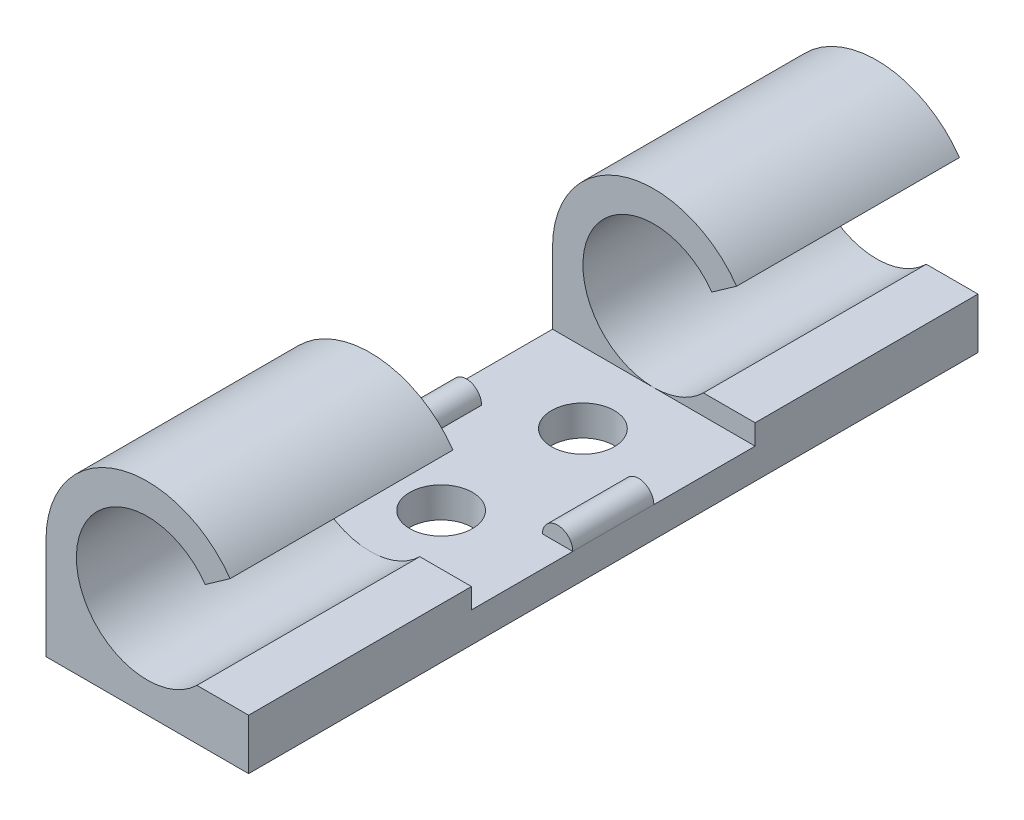
SolidWorks part; units mm, degrees
ref_plane "Plano frontal" through (0, 0, 0) normal (0, 0, 1) x (1, 0, 0)
ref_plane "Plano superior" through (0, 0, 0) normal (0, 1, 0) x (1, 0, 0)
ref_plane "Plano direito" through (0, 0, 0) normal (1, 0, 0) x (0, 0, -1)
sketch "Esboço1" plane through (0, 0, 0) normal (0, 0, 1) x (1, 0, 0)
  line L0 (-5, 0) -> (5, 0)
  line L1 (-5, 5) -> (5, 5)
  line L2 (-5, 5) -> (-5, -5)
  line L3 (-5, -5) -> (5, -5)
  line L4 (5, 5) -> (5, -5)
  line L5 (-5, 5) -> (5, -5) construction
  line L6 (-5, -5) -> (5, 5) construction
  circle A0 centre (0, 0) radius 5
  circle A2 centre (0, 0) radius 3.5
  point P0 (0, 0)
  point P12 (0, 0)
  dimension "D3" = 7
  dimension "D1" = 10
  dimension "D2" = 10
extrude "Ressalto-extrusão1" add sketch "Esboço1" along normal blind 11 contours A0 L2 L3 | A0 L3 L4 | A2 L0 A0 | A2 L0 A0
sketch "Esboço2" plane through (0, 0, 11) normal (0, 0, 1) x (1, 0, 0)
  line L0 (5, 0) -> (5, -5) construction
  line L1 (-5, -5) -> (5, -5)
  line L2 (-5, -5) -> (-5, -3.5)
  line L3 (-5, -3.5) -> (5, -3.5)
  line L4 (5, -5) -> (5, -3.5)
  line L5 (-5, -5) -> (5, -3.5) construction
  line L6 (-5, -3.5) -> (5, -5) construction
  circle A0 centre (0, 0) radius 3.5 construction
  point P4 (0, -4.25)
extrude "Ressalto-extrusão2" add sketch "Esboço2" along normal blind 7
sketch "Esboço3" plane through (0, 0, 18) normal (0, 0, 1) x (1, 0, 0)
  line L0 (5, -3.5) -> (0, -3.5) construction
  line L1 (5, -3.5) -> (0, -3.5) construction
  line L2 (0, 0) -> (0, -0.723) construction
  arc A0 (5, -3.5) -> (3.5, -3.5) centre (4.25, -3.5) ccw
  arc A1 (3.5, -3.5) -> (5, -3.5) centre (4.25, -3.5) ccw construction
  arc A2 (-5, -3.5) -> (-3.5, -3.5) centre (-4.25, -3.5) cw
  line M5 (5, -3.5) -> (-5, -3.5)
  dimension "D1" = 1.5
extrude "Ressalto-extrusão3" add sketch "Esboço3" against normal blind 2 contours A0 M5 | A2 M5
mirror "Espelhar1" about plane through (0, 0, 18) normal (0, 0, -1) of "Ressalto-extrusão2", "Ressalto-extrusão1", "Ressalto-extrusão3"
sketch "Esboço4" plane through (0, -3.5, 0) normal (0, 1, 0) x (1, 0, 0)
  line L0 (0, -11) -> (0, -18) construction
  line L2 (-3.5, -18) -> (3.5, -18) construction
  line L3 (-3.5, -16) -> (-3.5, -20) construction
  line L4 (3.5, -16) -> (3.5, -20) construction
  line L5 (-5, -11) -> (5, -11) construction
  circle A0 centre (0, -14.5) radius 1.55
  circle A1 centre (0, -21.5) radius 1.55
  point P13 (0, 0)
  dimension "D1" = 3.1
extrude "Corte-extrusão1" cut sketch "Esboço4" against normal blind 2
sketch "Esboço5" plane through (0, 0, 36) normal (0, 0, 1) x (1, 0, 0)
  line L0 (5, -2.5) -> (2.4495, -2.5)
  line L1 (5, 0) -> (5, -5) construction
  line L2 (-5, -5) -> (5, -5) construction
  line L3 (4.5826, 2) -> (2.839, 2) construction
  line L4 (2.839, 2) -> (4.0875, 2.8796)
  line L5 (0, 0) -> (2.839, 2) construction
  circle A0 centre (0, 0) radius 3.5 construction
  arc A1 (5, 0) -> (-5, 0) centre (0, 0) ccw construction
  point P16 (0, 0)
  circle M4 centre (0, 0) radius 3.5
  line M6 (5, -5) -> (5, 0)
  arc M7 (5, 0) -> (-5, 0) centre (0, 0) ccw
  dimension "D1" = 2.5
  dimension "D2" = 4.5
  dimension "D3" = 35.164
extrude "Corte-extrusão2" cut sketch "Esboço5" against normal through all contours L4 L0 M4 M6 M7
equation "\"D2@Esboço1\"=\"D1@Esboço1\""
equation "\"D3@Esboço1\"=\"D1@Esboço1\"-3"
